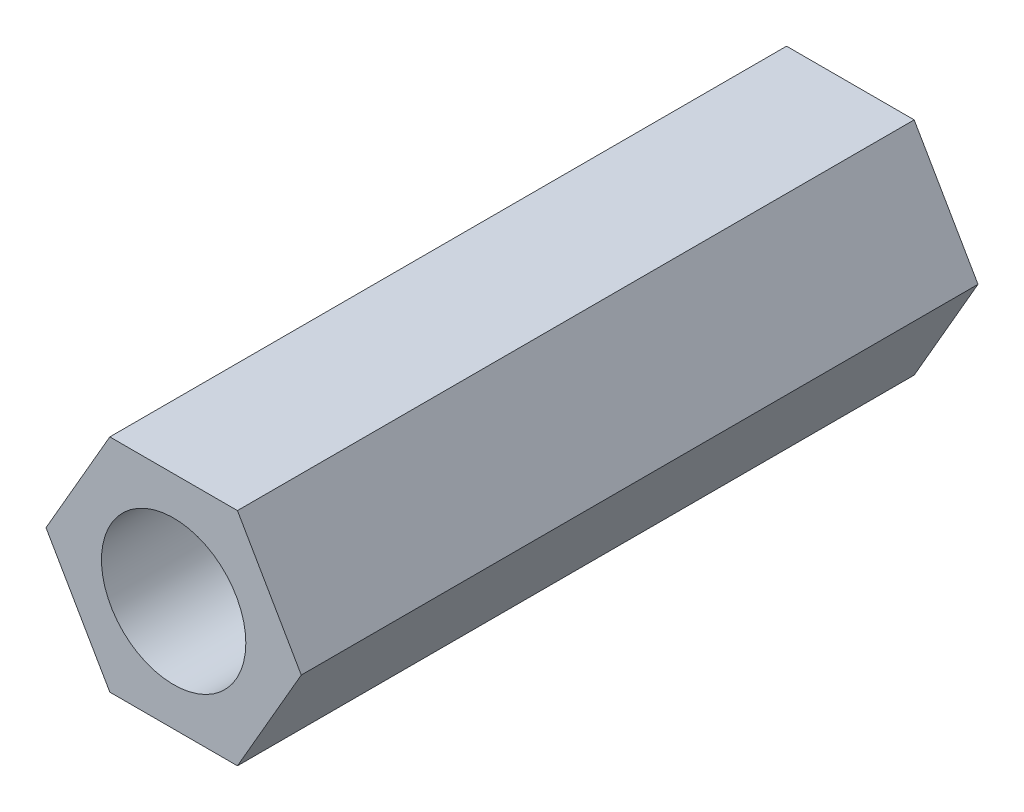
SolidWorks part; units mm, degrees
material "黄铜"
ref_plane "前视基准面" through (0, 0, 0) normal (0, 0, 1) x (1, 0, 0)
ref_plane "上视基准面" through (0, 0, 0) normal (0, 1, 0) x (1, 0, 0)
ref_plane "右视基准面" through (0, 0, 0) normal (1, 0, 0) x (0, 0, -1)
sketch "草图1" plane through (0, 0, 0) normal (0, 0, 1) x (1, 0, 0)
  line L1 (2.829, 0) -> (1.4145, 2.45)
  line L2 (1.4145, 2.45) -> (-1.4145, 2.45)
  line L3 (-1.4145, 2.45) -> (-2.829, 0)
  line L4 (-2.829, 0) -> (-1.4145, -2.45)
  line L5 (-1.4145, -2.45) -> (1.4145, -2.45)
  line L6 (1.4145, -2.45) -> (2.829, 0)
  circle A0 centre (0, 0) radius 1.6
  circle A1 centre (0, 0) radius 2.45 construction
  dimension "D1" = 3.2
  dimension "D2" = 4.9
extrude "凸台-拉伸1" add sketch "草图1" along normal blind 15
